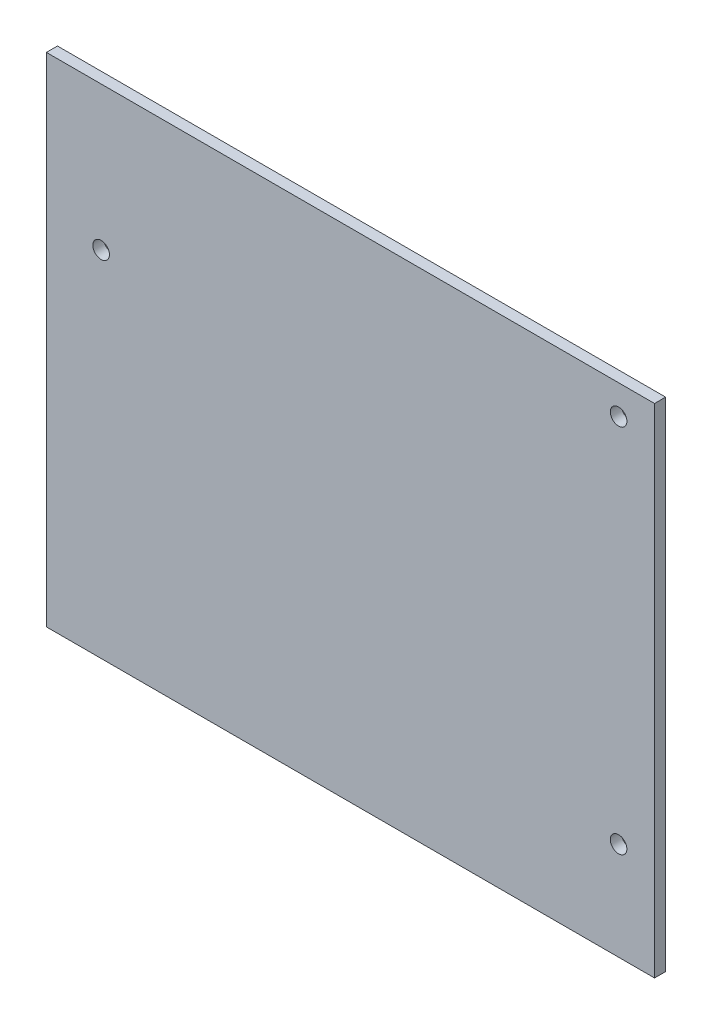
SolidWorks part; units mm, degrees
ref_plane "Plan de face" through (0, 0, 0) normal (0, 0, 1) x (1, 0, 0)
ref_plane "Plan de dessus" through (0, 0, 0) normal (0, 1, 0) x (1, 0, 0)
ref_plane "Plan de droite" through (0, 0, 0) normal (1, 0, 0) x (0, 0, -1)
sketch "Esquisse1" plane through (0, 0, 0) normal (0, 0, 1) x (1, 0, 0)
  line L1 (-55, -45) -> (55, -45)
  line L2 (-55, -45) -> (-55, 45)
  line L3 (-55, 45) -> (55, 45)
  line L4 (55, -45) -> (55, 45)
  line L5 (-55, -45) -> (55, 45) construction
  line L6 (-55, 45) -> (55, -45) construction
  circle A0 centre (48.5, 39.7) radius 1.5
  circle A1 centre (-45.1, 19) radius 1.5
  circle A2 centre (48.5, -27.3) radius 1.5
  point P0 (0, 0)
  dimension "D3" = 3
  dimension "D4" = 3
  dimension "D5" = 3
  dimension "D1" = 110
  dimension "D2" = 90
  dimension "D6" = 84.7
  dimension "D7" = 6.5
  dimension "D8" = 6.5
  dimension "D9" = 17.7
  dimension "D10" = 100.1
  dimension "D11" = 64
extrude "Boss.-Extru.1" add sketch "Esquisse1" along normal blind 2
